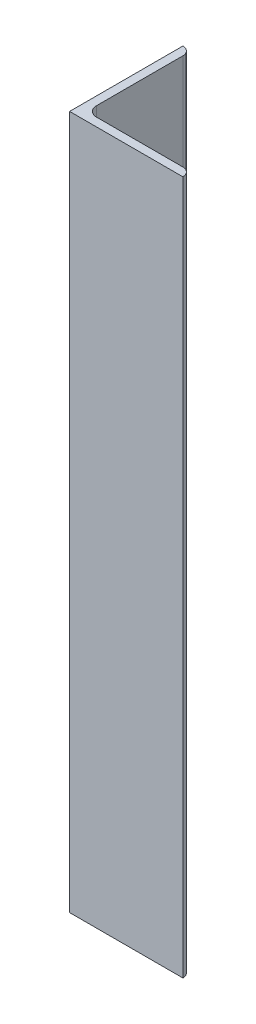
SolidWorks part; units mm, degrees
ref_plane "Front Plane" through (0, 0, 0) normal (0, 0, 1) x (1, 0, 0)
ref_plane "Top Plane" through (0, 0, 0) normal (0, 1, 0) x (1, 0, 0)
ref_plane "Right Plane" through (0, 0, 0) normal (1, 0, 0) x (0, 0, -1)
sketch3d "3DSketch1"
  line L0 (0, 0, 0) -> (0, 245, 0)
  dimension "D1" = 245
other "Iron V40X40X3(1)"
ref_plane "Plane1" through (0, 0, 0) normal (0, 1, 0) x (1, 0, 0)
sketch "Sketch1" plane through (0, 0, 0) normal (0, 1, 0) x (1, 0, 0)
  line L0 (0, 0) -> (0, 40)
  line L1 (0, 20) -> (3, 20) construction
  line L2 (3, 37) -> (3, 6.5)
  line L3 (6.5, 3) -> (37, 3)
  line L4 (20, 3) -> (20, 0) construction
  line L5 (40, 0) -> (0, 0)
  arc A0 (40, 0) -> (37, 3) centre (37, 0) ccw
  arc A1 (0, 40) -> (3, 37) centre (0, 37) cw
  arc A2 (6.5, 3) -> (3, 6.5) centre (6.5, 6.5) cw
  point P10 (20, 0)
  point P14 (0, 20)
  point P15 (3, 20)
  point P16 (20, 3)
  point P17 (3, 40)
  point P18 (40, 3)
  point P21 (0, 0)
  dimension "D2" = 3
  dimension "D3" = 40
  dimension "Radius_1" = 3.5
  dimension "D1" = 3
